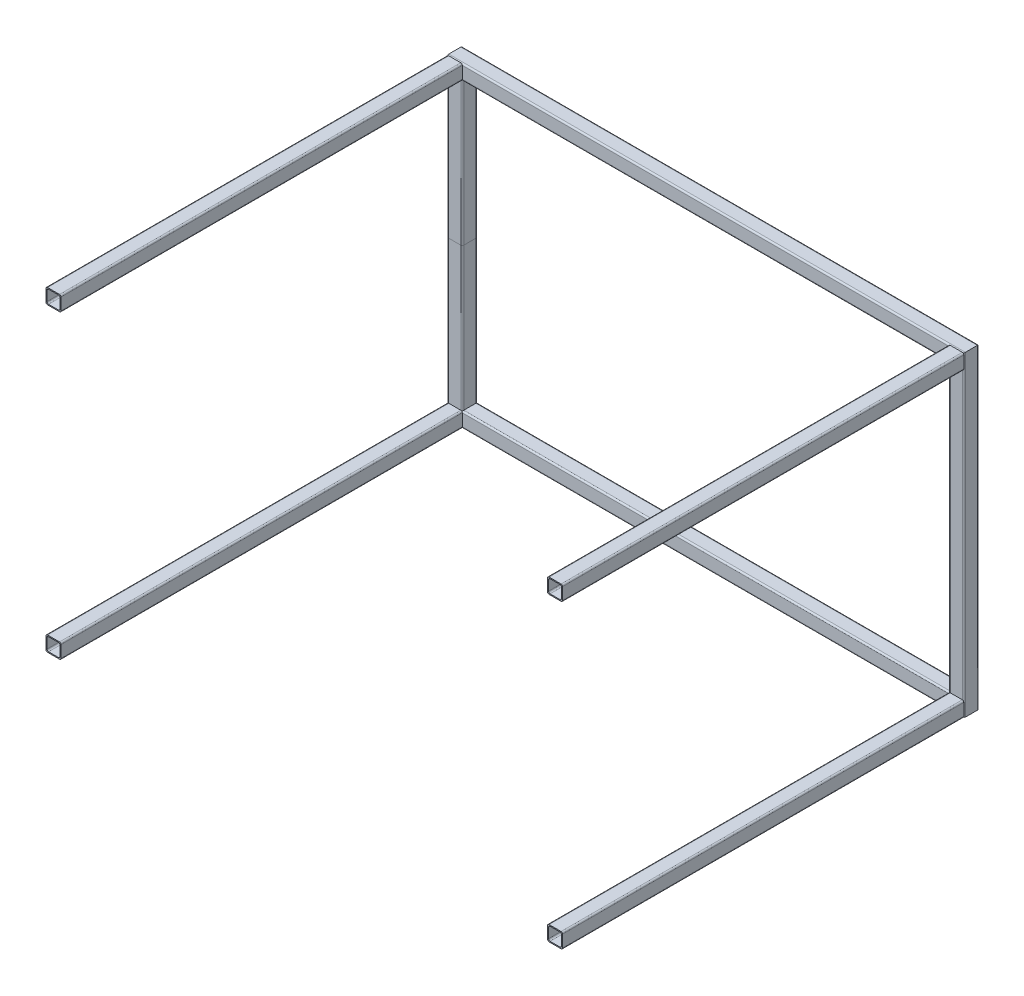
SolidWorks part; units mm, degrees
ref_plane "Plan de face" through (0, 0, 0) normal (0, 0, 1) x (1, 0, 0)
ref_plane "Plan de dessus" through (0, 0, 0) normal (0, 1, 0) x (1, 0, 0)
ref_plane "Plan de droite" through (0, 0, 0) normal (1, 0, 0) x (0, 0, -1)
sketch "Esquisse1" plane through (0, 0, 0) normal (0, 0, 1) x (1, 0, 0)
  line L1 (-600, -400) -> (600, -400)
  line L2 (-600, -400) -> (-600, 400)
  line L3 (-600, 400) -> (600, 400)
  line L4 (600, -400) -> (600, 400)
  line L5 (-600, -400) -> (600, 400) construction
  line L6 (-600, 400) -> (600, -400) construction
  point P0 (0, 0)
  dimension "D1" = 1200
  dimension "D2" = 800
sketch "Esquisse2" plane through (0, 0, 0) normal (0, 1, 0) x (1, 0, 0)
  line L0 (-600, 0) -> (600, 0) construction
  line L1 (-512, -15) -> (-488, -15)
  line L2 (-515, -12) -> (-515, 12)
  line L3 (-512, 15) -> (-488, 15)
  line L4 (-485, -12) -> (-485, 12)
  line L5 (-515, -15) -> (-485, 15) construction
  line L6 (-515, 15) -> (-485, -15) construction
  line L7 (-600, 0) -> (600, 0) construction
  line L9 (-510, -13) -> (-490, -13)
  line L10 (-513, -10) -> (-513, 10)
  line L11 (-510, 13) -> (-490, 13)
  line L12 (-487, -10) -> (-487, 10)
  line L13 (-513, -13) -> (-487, 13) construction
  line L14 (-513, 13) -> (-487, -13) construction
  arc A0 (-490, -13) -> (-487, -10) centre (-490, -10) ccw
  arc A1 (-513, 10) -> (-510, 13) centre (-510, 10) cw
  arc A2 (-510, -13) -> (-513, -10) centre (-510, -10) cw
  arc A3 (-490, 13) -> (-487, 10) centre (-490, 10) cw
  arc A4 (-488, -15) -> (-485, -12) centre (-488, -12) ccw
  arc A5 (-512, -15) -> (-515, -12) centre (-512, -12) cw
  arc A6 (-488, 15) -> (-485, 12) centre (-488, 12) cw
  arc A7 (-515, 12) -> (-512, 15) centre (-512, 12) cw
  point P0 (-500, 0)
  point P9 (-500, 0)
  dimension "D5" = 3
  dimension "D1" = 30
  dimension "D2" = 30
  dimension "D3" = 26
  dimension "D4" = 26
sweep "Balayage1" add profiles "Esquisse2" path "Esquisse1"
sketch "Esquisse3" plane through (0, 0, 15) normal (0, 0, 1) x (1, 0, 0)
  line L0 (-515, 315) -> (515, 315) construction
  line L1 (-512, 285) -> (-488, 285)
  line L2 (-515, 288) -> (-515, 312)
  line L3 (-512, 315) -> (-488, 315)
  line L4 (-485, 288) -> (-485, 312)
  line L5 (-500, 315) -> (-500, 285) construction
  line L6 (-515, 300) -> (-485, 300) construction
  line L7 (-488, 288) -> (-512, 312) construction
  line L8 (-510, 287) -> (-490, 287)
  line L9 (-513, 290) -> (-513, 310)
  line L10 (-510, 313) -> (-490, 313)
  line L11 (-487, 290) -> (-487, 310)
  line L12 (-500, 313) -> (-500, 287) construction
  line L13 (-513, 300) -> (-487, 300) construction
  line L14 (0, 354.9683) -> (0, -415.7461) construction
  line L15 (-462.9458, 0) -> (284.4919, 0) construction
  line L16 (513, 300) -> (487, 300) construction
  line L17 (500, 313) -> (500, 287) construction
  line L18 (515, 300) -> (485, 300) construction
  line L19 (500, 315) -> (500, 285) construction
  line L20 (487, 290) -> (487, 310)
  line L21 (510, 313) -> (490, 313)
  line L22 (513, 290) -> (513, 310)
  line L23 (510, 287) -> (490, 287)
  line L24 (485, 288) -> (485, 312)
  line L25 (512, 315) -> (488, 315)
  line L26 (515, 288) -> (515, 312)
  line L27 (512, 285) -> (488, 285)
  line L28 (-512, -315) -> (-488, -315)
  line L29 (-485, -288) -> (-485, -312)
  line L30 (-512, -285) -> (-488, -285)
  line L31 (-510, -287) -> (-490, -287)
  line L32 (-510, -313) -> (-490, -313)
  line L33 (-487, -290) -> (-487, -310)
  line L34 (-513, -290) -> (-513, -310)
  line L35 (-515, -288) -> (-515, -312)
  line L36 (500, -315) -> (500, -285) construction
  line L37 (515, -300) -> (485, -300) construction
  line L38 (500, -313) -> (500, -287) construction
  line L39 (513, -300) -> (487, -300) construction
  line L40 (512, -285) -> (488, -285)
  line L41 (515, -288) -> (515, -312)
  line L42 (512, -315) -> (488, -315)
  line L43 (485, -288) -> (485, -312)
  line L44 (510, -287) -> (490, -287)
  line L45 (513, -290) -> (513, -310)
  line L46 (510, -313) -> (490, -313)
  line L47 (487, -290) -> (487, -310)
  arc A0 (-510, 287) -> (-513, 290) centre (-510, 290) cw
  arc A1 (-512, 285) -> (-515, 288) centre (-512, 288) cw
  arc A2 (-488, 285) -> (-485, 288) centre (-488, 288) ccw
  arc A3 (-490, 287) -> (-487, 290) centre (-490, 290) ccw
  arc A4 (-513, 310) -> (-510, 313) centre (-510, 310) cw
  arc A5 (-490, 313) -> (-487, 310) centre (-490, 310) cw
  arc A6 (-488, 315) -> (-485, 312) centre (-488, 312) cw
  arc A7 (-515, 312) -> (-512, 315) centre (-512, 312) cw
  arc A8 (515, 312) -> (512, 315) centre (512, 312) ccw
  arc A9 (488, 315) -> (485, 312) centre (488, 312) ccw
  arc A10 (490, 313) -> (487, 310) centre (490, 310) ccw
  arc A11 (513, 310) -> (510, 313) centre (510, 310) ccw
  arc A12 (490, 287) -> (487, 290) centre (490, 290) cw
  arc A13 (488, 285) -> (485, 288) centre (488, 288) cw
  arc A14 (512, 285) -> (515, 288) centre (512, 288) ccw
  arc A15 (510, 287) -> (513, 290) centre (510, 290) ccw
  arc A16 (-488, -315) -> (-485, -312) centre (-488, -312) ccw
  arc A17 (-488, -285) -> (-485, -288) centre (-488, -288) cw
  arc A18 (-490, -287) -> (-487, -290) centre (-490, -290) cw
  arc A19 (-490, -313) -> (-487, -310) centre (-490, -310) ccw
  arc A20 (-513, -310) -> (-510, -313) centre (-510, -310) ccw
  arc A21 (-510, -287) -> (-513, -290) centre (-510, -290) ccw
  arc A22 (-515, -312) -> (-512, -315) centre (-512, -312) ccw
  arc A23 (-512, -285) -> (-515, -288) centre (-512, -288) ccw
  arc A24 (510, -287) -> (513, -290) centre (510, -290) cw
  arc A25 (512, -285) -> (515, -288) centre (512, -288) cw
  arc A26 (488, -285) -> (485, -288) centre (488, -288) ccw
  arc A27 (490, -287) -> (487, -290) centre (490, -290) ccw
  arc A28 (513, -310) -> (510, -313) centre (510, -310) cw
  arc A29 (490, -313) -> (487, -310) centre (490, -310) cw
  arc A30 (488, -315) -> (485, -312) centre (488, -312) cw
  arc A31 (515, -312) -> (512, -315) centre (512, -312) cw
  point P0 (-500, 300)
  point P7 (-500, 300)
  point P17 (-513, 287)
  point P23 (-515, 285)
  point P28 (-487, 287)
  point P31 (-513, 313)
  point P36 (-485, 315)
  point P39 (-515, 315)
  point P76 (515, 315)
  point P77 (485, 315)
  point P78 (513, 313)
  point P79 (487, 287)
  point P80 (515, 285)
  point P81 (513, 287)
  point P82 (500, 300)
  point P107 (-515, -315)
  point P108 (-513, -313)
  point P109 (-515, -285)
  point P110 (-513, -287)
  point P146 (500, -300)
  point P147 (513, -287)
  point P148 (515, -285)
  point P149 (487, -287)
  point P150 (513, -313)
  point P151 (485, -315)
  point P152 (515, -315)
  dimension "D5" = 3
  dimension "D1" = 30
  dimension "D2" = 30
  dimension "D3" = 26
  dimension "D4" = 26
extrude "Boss.-Extru.1" add sketch "Esquisse3" along normal blind 800
